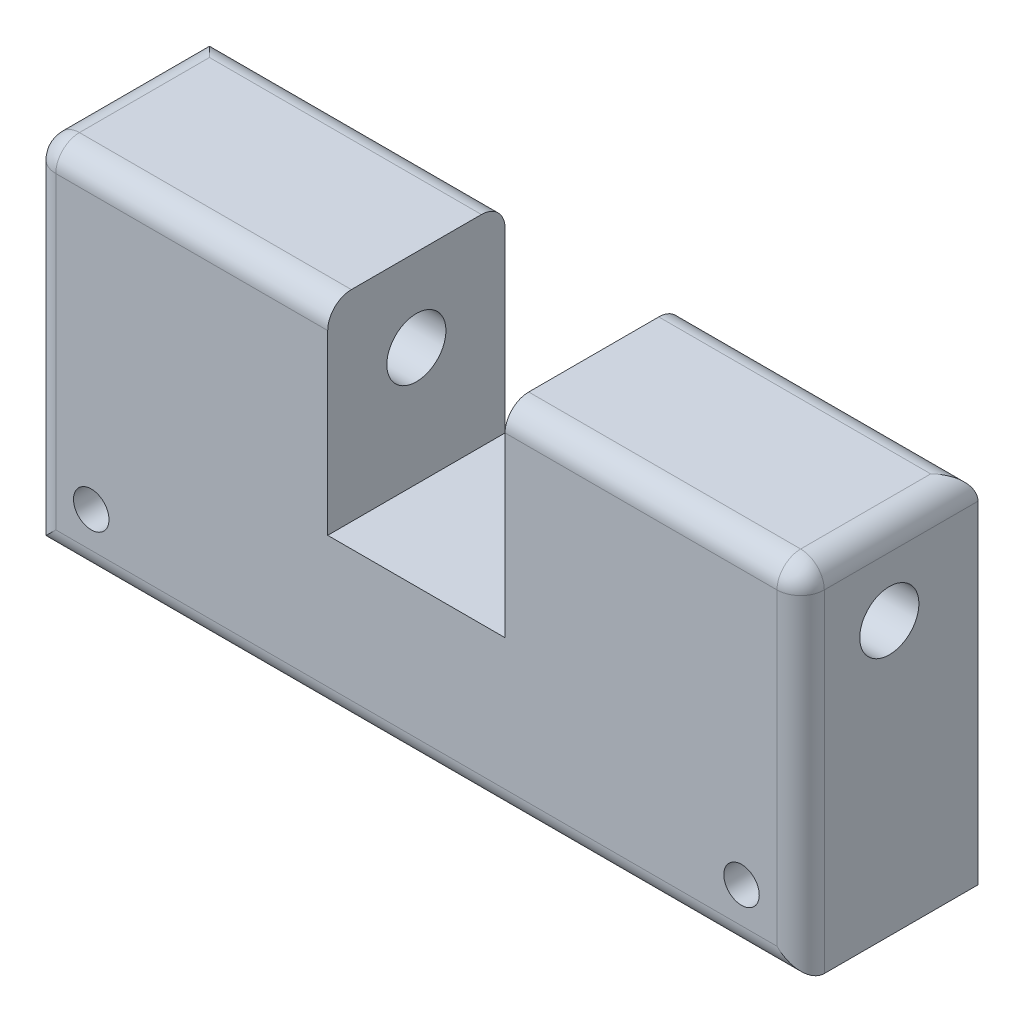
SolidWorks part; units mm, degrees
ref_plane "Front Plane" through (0, 0, 0) normal (0, 0, 1) x (1, 0, 0)
ref_plane "Top Plane" through (0, 0, 0) normal (0, 1, 0) x (1, 0, 0)
ref_plane "Right Plane" through (0, 0, 0) normal (1, 0, 0) x (0, 0, -1)
sketch "Sketch1" plane through (0, 0, 0) normal (0, 0, 1) x (1, 0, 0)
  line L0 (42.5, -5) -> (42.5, -14.5) construction
  line L1 (-22.5, -14.5) -> (42.5, -14.5)
  line L2 (-22.5, -14.5) -> (-22.5, 15.6)
  line L3 (-22.5, 15.6) -> (42.5, 15.6)
  line L4 (42.5, -14.5) -> (42.5, 15.6)
  line L5 (34.5, 2.6) -> (27.7, 2.6) construction
  circle A0 centre (-17.5, -9.5) radius 1.5
  circle A1 centre (37.5, -9.5) radius 1.5
  dimension "D1" = 0
  dimension "D2" = 13
extrude "Boss-Extrude1" add sketch "Sketch1" along normal blind 15
sketch "Sketch2" plane through (-22.5, 0, 0) normal (-1, 0, 0) x (0, 0, 1)
  line L0 (15, 15.6) -> (15, -14.5) construction
  line L1 (15, 15.6) -> (0, 15.6) construction
  circle A0 centre (7.5, 8.6) radius 2.5
  dimension "D1" = 5
  dimension "D2" = 7.5
  dimension "D3" = 7
extrude "Cut-Extrude1" cut sketch "Sketch2" against normal blind 75
sketch "Sketch3" plane through (0, 0, 15) normal (0, 0, 1) x (1, 0, 0)
  line L0 (42.5, 15.6) -> (-22.5, 15.6) construction
  line L1 (2.5, 15.6) -> (17.5, 15.6)
  line L2 (2.5, 15.6) -> (2.5, -1.4)
  line L3 (2.5, -1.4) -> (17.5, -1.4)
  line L4 (17.5, 15.6) -> (17.5, -1.4)
  line L5 (10, 15.6) -> (10, -27.8113) construction
  dimension "D1" = 17
  dimension "D2" = 15
  dimension "D3" = 7.5
extrude "Cut-Extrude2" cut sketch "Sketch3" against normal blind 75
fillet "Fillet2" radius 2 9 edges at (-22.5, 15.6, 7.5) (42.5, 15.6, 7.5) (30, 15.6, 0) (-10, 15.6, 0) (30, 15.6, 15) (-10, 15.6, 15) (10, -14.5, 15) (42.5, 0.55, 15) (-22.5, 0.55, 15)
